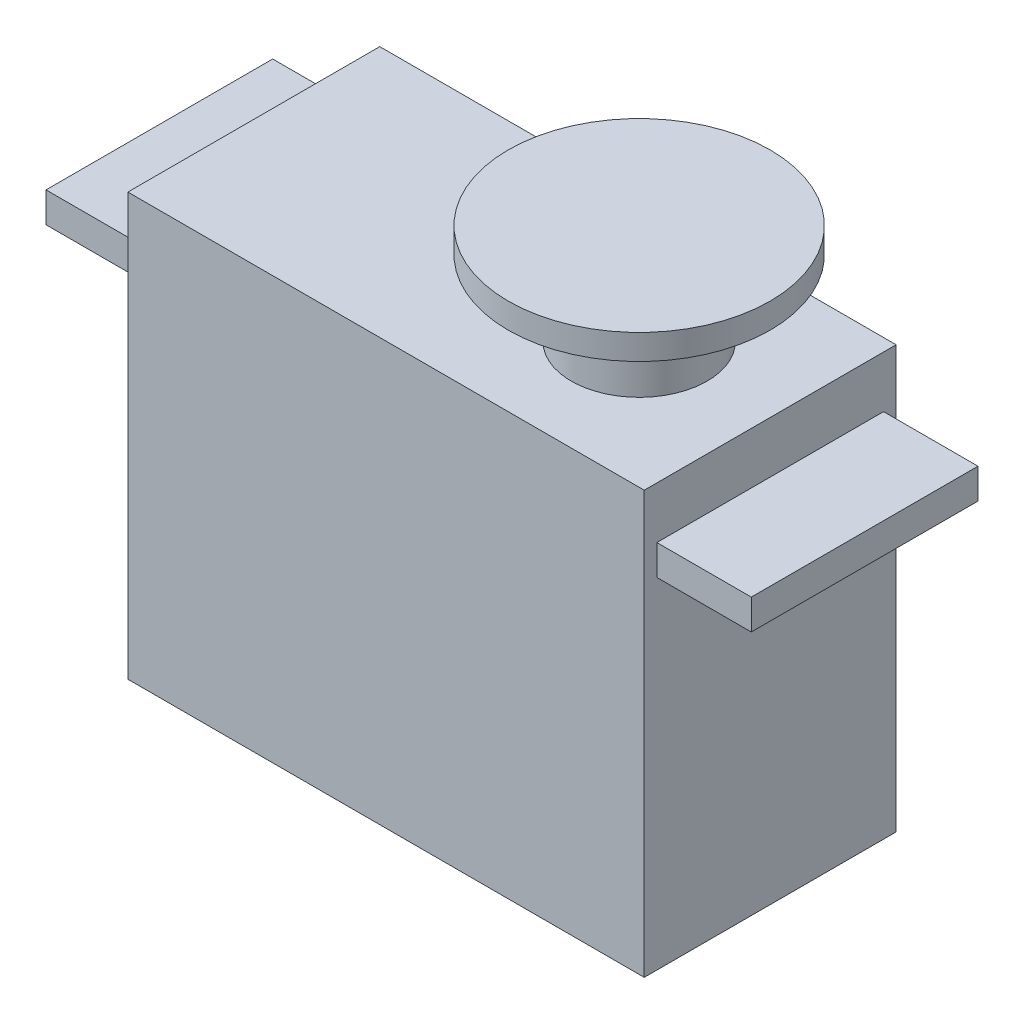
SolidWorks part; units mm, degrees
ref_plane "Front Plane" through (0, 0, 0) normal (0, 0, 1) x (1, 0, 0)
ref_plane "Top Plane" through (0, 0, 0) normal (0, 1, 0) x (1, 0, 0)
ref_plane "Right Plane" through (0, 0, 0) normal (1, 0, 0) x (0, 0, -1)
sketch "Sketch1" plane through (0, 0, 0) normal (0, 0, 1) x (1, 0, 0)
  line L0 (0, 0) -> (41, 0)
  line L1 (41, 0) -> (41, 33.5)
  line L2 (41, 33.5) -> (0, 33.5)
  line L3 (0, 33.5) -> (0, 0)
  dimension "D1" = 33.5
  dimension "D2" = 41
extrude "Boss-Extrude1" add sketch "Sketch1" along normal blind 20
ref_plane "Plane1" through (20.5, 0, 0) normal (1, 0, 0) x (0, 0, -1)
sketch "Sketch3" plane through (41, 0, 0) normal (1, 0, 0) x (0, 0, -1)
  line L0 (-20, 0) -> (-20, 33.5) construction
  line L1 (-19, 27) -> (-1, 27)
  line L2 (-19, 27) -> (-19, 29.4)
  line L3 (-19, 29.4) -> (-1, 29.4)
  line L4 (-1, 27) -> (-1, 29.4)
  line L5 (-20, 0) -> (0, 0) construction
  dimension "D1" = 18
  dimension "D2" = 1
  dimension "D3" = 2.4
  dimension "D4" = 27
extrude "Boss-Extrude2" add sketch "Sketch3" along normal blind 7.5
mirror "Mirror1" about plane through (20.5, 0, 0) normal (1, 0, 0) of "Boss-Extrude2"
sketch "Sketch4" plane through (0, 0, 0) normal (0, 0, 1) x (1, 0, 0)
  line L0 (30.6, 33.5) -> (30.6, 41.5)
  line L1 (41, 33.5) -> (0, 33.5) construction
  line L2 (30.6, 41.5) -> (41, 41.5)
  line L3 (41, 41.5) -> (41, 39.5)
  line L4 (41, 39.5) -> (36, 39.5)
  line L5 (36, 39.5) -> (36, 33.5)
  line L6 (30.6, 33.5) -> (36, 33.5)
  line L7 (41, 0) -> (41, 33.5) construction
  dimension "D1" = 6
  dimension "D2" = 2
  dimension "D3" = 10.4
  dimension "D4" = 5
  dimension "D5" = 10.4
ref_plane "Plane2" through (0, 0, 10) normal (0, 0, 1) x (1, 0, 0)
sketch "Sketch5" plane through (0, 0, 10) normal (0, 0, 1) x (1, 0, 0)
  line L0 (30.6, 33.5) -> (30.6, 41.5)
  line L1 (30.6, 41.5) -> (41, 41.5)
  line L2 (41, 41.5) -> (41, 39.5)
  line L3 (41, 39.5) -> (36, 39.5)
  line L4 (36, 39.5) -> (36, 33.5)
  line L5 (36, 33.5) -> (30.6, 33.5)
revolve "Revolve1" add sketch "Sketch5" angle 360 about L0
